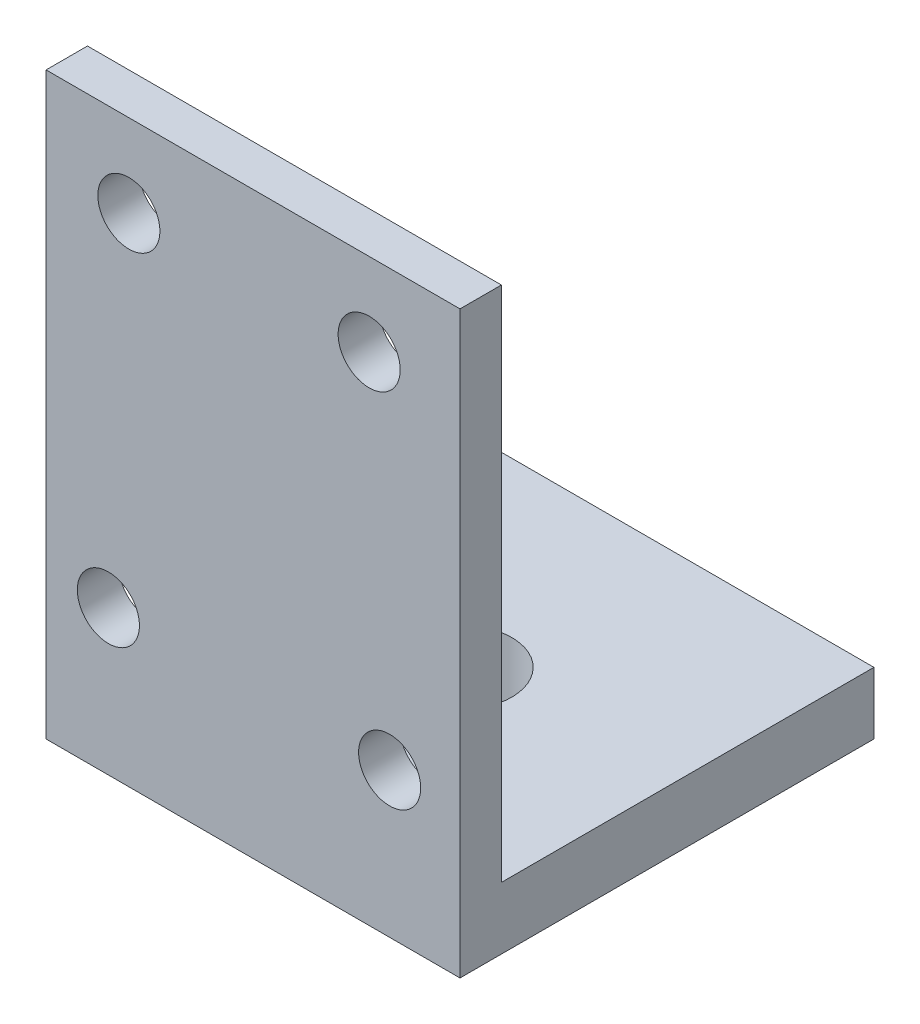
SolidWorks part; units mm, degrees
ref_plane "Front Plane" through (0, 0, 0) normal (0, 0, 1) x (1, 0, 0)
ref_plane "Top Plane" through (0, 0, 0) normal (0, 1, 0) x (1, 0, 0)
ref_plane "Right Plane" through (0, 0, 0) normal (1, 0, 0) x (0, 0, -1)
sketch "Sketch1" plane through (0, 0, 0) normal (0, 1, 0) x (1, 0, 0)
  line L1 (0, 0) -> (20, 0)
  line L2 (0, 0) -> (0, 20)
  line L3 (0, 20) -> (20, 20)
  line L4 (20, 0) -> (20, 20)
  circle A0 centre (10, 10) radius 2.5
  dimension "D3" = 5
  dimension "D1" = 20
  dimension "D2" = 20
  dimension "D4" = 10
  dimension "D5" = 10
extrude "Boss-Extrude1" add sketch "Sketch1" along normal blind 3
sketch "Sketch2" plane through (0, 3, 0) normal (0, 1, 0) x (1, 0, 0)
  line L0 (0, 0) -> (20, 0) construction
  line L1 (0, 0) -> (20, 0)
  line L2 (0, 0) -> (0, 2)
  line L3 (0, 2) -> (20, 2)
  line L4 (20, 0) -> (20, 2)
  point P6 (0, 0)
  point P8 (0, 0)
  dimension "D1" = 2
extrude "Boss-Extrude2" add sketch "Sketch2" along normal blind 25
sketch "Sketch3" plane through (0, 0, 0) normal (0, 0, 1) x (1, 0, 0)
  line L0 (0, 28) -> (0, 3) construction
  line L1 (0, 28) -> (20, 28) construction
  line L2 (9.8051, 28) -> (9.8051, 0) construction
  line L3 (0, 0) -> (20, 0) construction
  circle A0 centre (4, 24) radius 1.5
  circle A1 centre (16.6, 7) radius 1.5
  circle A2 centre (3.0102, 7) radius 1.5
  circle A3 centre (15.6102, 24) radius 1.5
  dimension "D3" = 3
  dimension "D4" = 3
  dimension "D1" = 12.6
  dimension "D2" = 17
  dimension "D5" = 4
  dimension "D6" = 4
extrude "Cut-Extrude1" cut sketch "Sketch3" against normal blind 25
